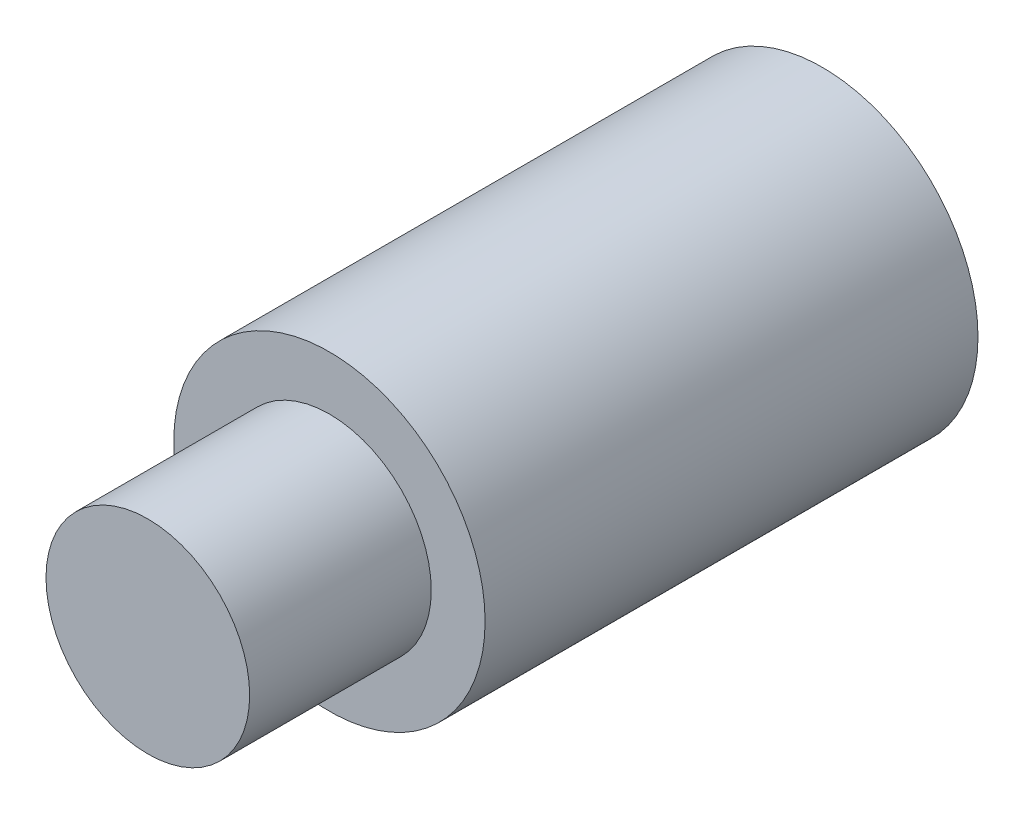
SolidWorks part; units mm, degrees
ref_plane "Ebene vorne" through (0, 0, 0) normal (0, 0, 1) x (1, 0, 0)
ref_plane "Ebene oben" through (0, 0, 0) normal (0, 1, 0) x (1, 0, 0)
ref_plane "Ebene rechts" through (0, 0, 0) normal (1, 0, 0) x (0, 0, -1)
sketch "Skizze1" plane through (0, 0, 0) normal (0, 0, 1) x (1, 0, 0)
  circle A0 centre (0, 0) radius 6
  dimension "D1" = 12
extrude "Aufsatz-Linear austragen1" add sketch "Skizze1" along normal blind 19
sketch "Skizze2" plane through (0, 0, 19) normal (0, 0, 1) x (1, 0, 0)
  circle A0 centre (0, 0) radius 3.925
  dimension "D1" = 7.85
extrude "Aufsatz-Linear austragen2" add sketch "Skizze2" along normal blind 7
